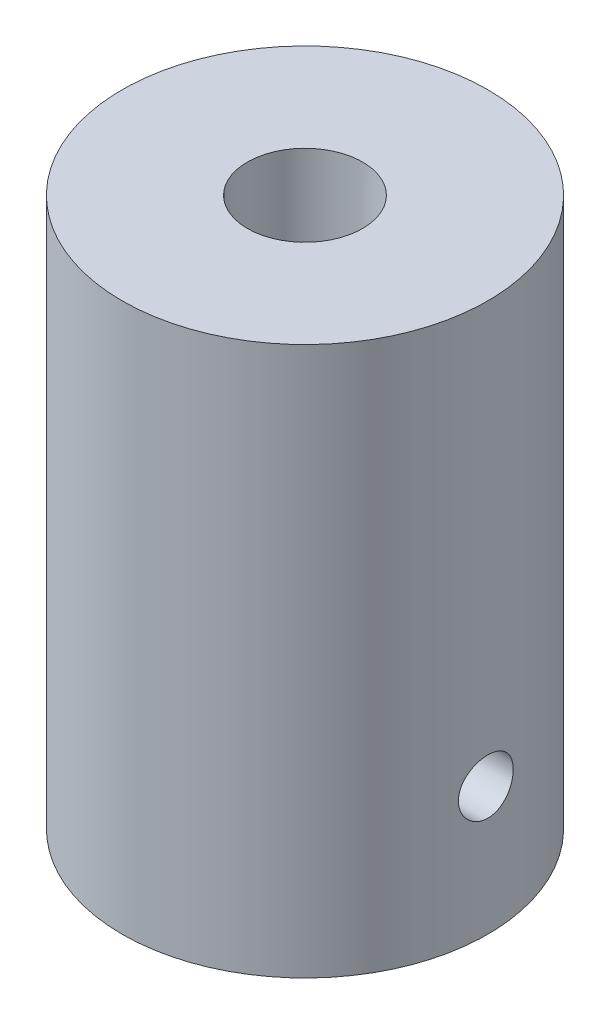
SolidWorks part; units mm, degrees
ref_plane "前视基准面" through (0, 0, 0) normal (0, 0, 1) x (1, 0, 0)
ref_plane "上视基准面" through (0, 0, 0) normal (0, 1, 0) x (1, 0, 0)
ref_plane "右视基准面" through (0, 0, 0) normal (1, 0, 0) x (0, 0, -1)
sketch "草图1" plane through (0, 0, 0) normal (0, 1, 0) x (1, 0, 0)
  circle A0 centre (0, 0) radius 3.15
  circle A1 centre (0, 0) radius 10
  dimension "D1" = 6.3
  dimension "D2" = 20
extrude "凸台-拉伸1" add sketch "草图1" along normal blind 30
sketch "草图2" plane through (0, 0, 0) normal (1, 0, 0) x (0, 0, -1)
  line L0 (-10, 0) -> (10, 0) construction
  circle A0 centre (0, 7) radius 1.5
  dimension "D2" = 3
  dimension "D4" = 7
extrude "切除-拉伸1" cut sketch "草图2" against normal through all both and the other way through all
sketch "草图3" plane through (0, 0, 0) normal (0, 0, 1) x (1, 0, 0)
  line L0 (10, 30) -> (-10, 30) construction
  circle A0 centre (0, 24) radius 1.5
  dimension "D1" = 3
  dimension "D2" = 6
extrude "切除-拉伸2" cut sketch "草图3" against normal through all
sketch "草图4" plane through (0, 0, 0) normal (0, -1, 0) x (1, 0, 0)
  circle A0 centre (0, 0) radius 6.15
  dimension "D1" = 12.3
extrude "切除-拉伸3" cut sketch "草图4" against normal offset from surface (18 mm away) 12 up to face at (0, 30, 10)
sketch "草图5" plane through (0, 0, 0) normal (0, 0, 1) x (1, 0, 0)
  circle A0 centre (0, 24) radius 3
  dimension "D1" = 6
extrude "切除-拉伸4" cut sketch "草图5" along normal blind 3 from offset 10
